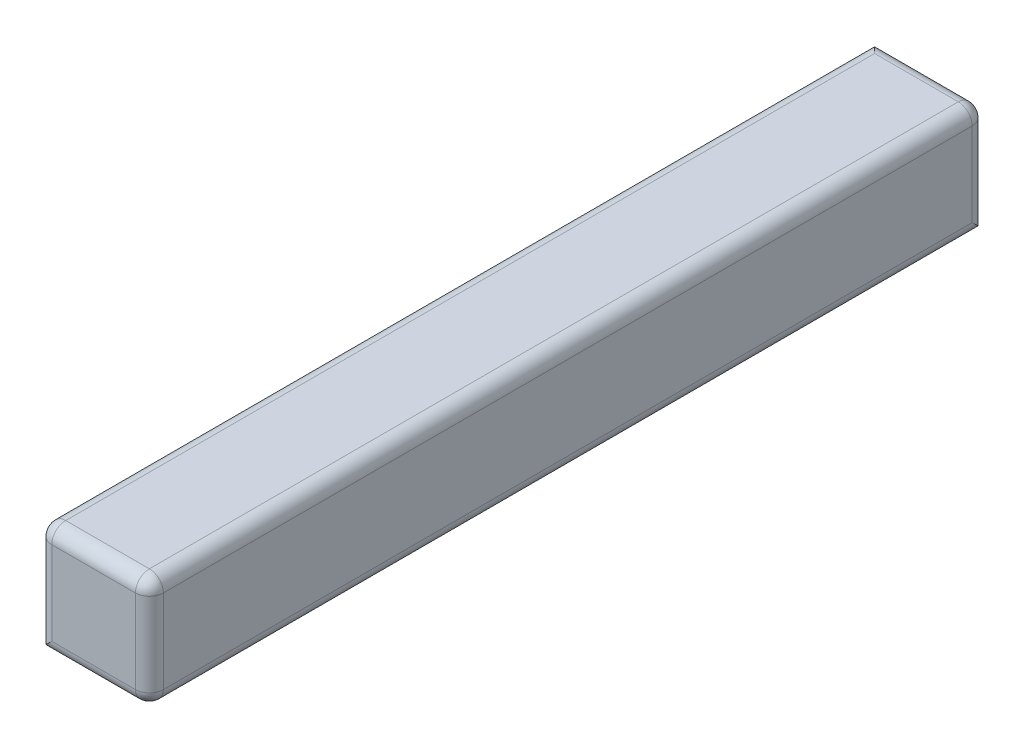
SolidWorks part; units mm, degrees
ref_plane "Front Plane" through (0, 0, 0) normal (0, 0, 1) x (1, 0, 0)
ref_plane "Top Plane" through (0, 0, 0) normal (0, 1, 0) x (1, 0, 0)
ref_plane "Right Plane" through (0, 0, 0) normal (1, 0, 0) x (0, 0, -1)
sketch "Sketch1" plane through (0, 0, 0) normal (0, 1, 0) x (1, 0, 0)
  line L1 (-16.9668, 13.2927) -> (-12.9668, 13.2927)
  line L2 (-16.9668, 13.2927) -> (-16.9668, -16.7073)
  line L3 (-16.9668, -16.7073) -> (-12.9668, -16.7073)
  line L4 (-12.9668, 13.2927) -> (-12.9668, -16.7073)
  dimension "D1" = 4
  dimension "D2" = 30
extrude "Boss-Extrude1" add sketch "Sketch1" along normal blind 4
fillet "Fillet1" radius 0.5 9 edges at (-14.9668, 0, 16.7073) (-12.9668, 0, 1.7073) (-16.9668, 4, 1.7073) (-14.9668, 4, 16.7073) (-12.9668, 4, 1.7073) (-14.9668, 4, -13.2927) (-12.9668, 2, -13.2927) (-12.9668, 2, 16.7073) (-16.9668, 2, 16.7073)
equation "\"LegLength\" = 30"
equation "\"LegWidth\" = 4"
equation "\"LegHeight\"= 4"
equation "\"D1@Sketch1\"=\"LegWidth\""
equation "\"D2@Sketch1\"=\"LegLength\""
equation "\"D1@Boss-Extrude1\"=\"LegHeight\""
